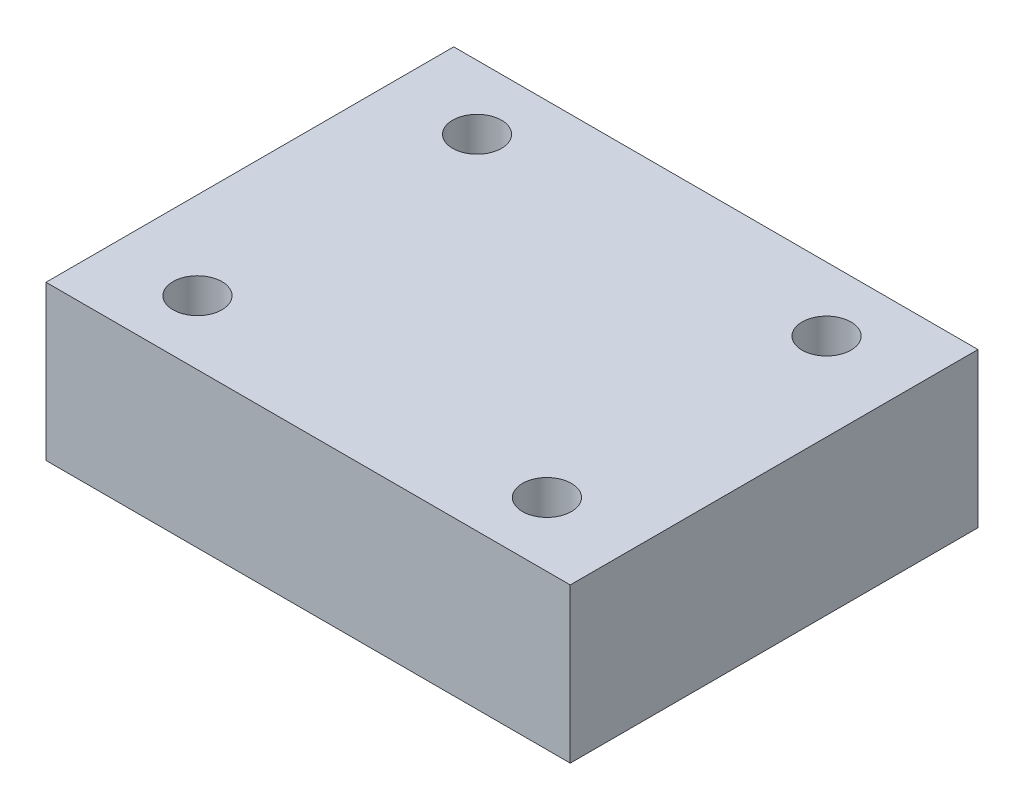
SolidWorks part; units mm, degrees
ref_plane "前视基准面" through (0, 0, 0) normal (0, 0, 1) x (1, 0, 0)
ref_plane "上视基准面" through (0, 0, 0) normal (0, 1, 0) x (1, 0, 0)
ref_plane "右视基准面" through (0, 0, 0) normal (1, 0, 0) x (0, 0, -1)
other "Configuration Table"
sketch "草图1" plane through (0, 0, 0) normal (0, 1, 0) x (1, 0, 0)
  line L1 (-22.5, -17.5) -> (22.5, -17.5)
  line L2 (-22.5, -17.5) -> (-22.5, 17.5)
  line L3 (-22.5, 17.5) -> (22.5, 17.5)
  line L4 (22.5, -17.5) -> (22.5, 17.5)
  line L5 (-22.5, -17.5) -> (22.5, 17.5) construction
  line L6 (-22.5, 17.5) -> (22.5, -17.5) construction
  circle A0 centre (-15, 12) radius 2.1
  circle A1 centre (15, 12) radius 2.1
  circle A2 centre (15, -12) radius 2.1
  circle A3 centre (-15, -12) radius 2.1
  point P0 (0, 0)
  dimension "D3" = 4.2
  dimension "D1" = 45
  dimension "D2" = 35
  dimension "D4" = 12
  dimension "D5" = 15
  dimension "D6" = 2
  dimension "D7" = 2
extrude "凸台-拉伸1" add sketch "草图1" along normal blind 13.25
